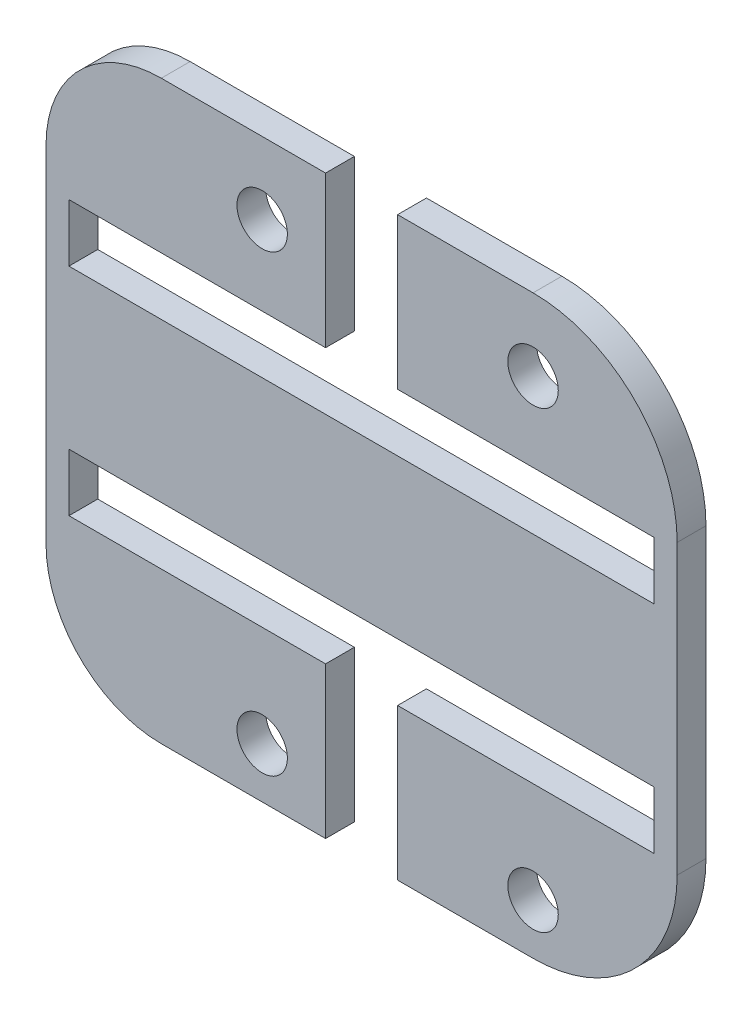
SolidWorks part; units mm, degrees
ref_plane "Alzado" through (0, 0, 0) normal (0, 0, 1) x (1, 0, 0)
ref_plane "Planta" through (0, 0, 0) normal (0, 1, 0) x (1, 0, 0)
ref_plane "Vista lateral" through (0, 0, 0) normal (1, 0, 0) x (0, 0, -1)
sketch "Croquis2" plane through (0, 0, 0) normal (0, 0, 1) x (1, 0, 0)
  line L1 (0, 0) -> (43.8, 0)
  line L2 (0, 0) -> (0, 40)
  line L3 (0, 40) -> (43.8, 40)
  line L4 (43.8, 0) -> (43.8, 40)
  line L5 (0, 0) -> (43.8, 40) construction
  line L6 (0, 40) -> (43.8, 0) construction
  line L7 (1.59, 29.5) -> (19.4, 29.5)
  line L8 (1.59, 29.5) -> (1.59, 25.5)
  line L9 (1.59, 25.5) -> (42.21, 25.5)
  line L10 (42.21, 29.5) -> (42.21, 25.5)
  line L11 (1.59, 29.5) -> (42.21, 25.5) construction
  line L12 (1.59, 25.5) -> (42.21, 29.5) construction
  line L16 (21.9, 40) -> (21.9, 0) construction
  line L17 (24.4, 29.5) -> (42.21, 29.5)
  line L18 (0, 20) -> (43.8, 20) construction
  line L19 (24.4, 0) -> (19.4, 0)
  line L20 (24.4, 0) -> (24.4, 10.5)
  line L21 (24.4, 40) -> (19.4, 40)
  line L22 (19.4, 0) -> (19.4, 10.5)
  line L23 (24.4, 0) -> (19.4, 40) construction
  line L24 (24.4, 40) -> (19.4, 0) construction
  line L25 (19.4, 29.5) -> (19.4, 40)
  line L26 (24.4, 29.5) -> (24.4, 40)
  line L27 (24.4, 10.5) -> (24.4, 0)
  line L28 (24.4, 10.5) -> (42.21, 10.5)
  line L29 (42.21, 10.5) -> (42.21, 14.5)
  line L30 (1.59, 14.5) -> (42.21, 14.5)
  line L31 (1.59, 10.5) -> (1.59, 14.5)
  line L32 (1.59, 10.5) -> (19.4, 10.5)
  line L33 (19.4, 10.5) -> (19.4, 0)
  line L34 (24.4, 0) -> (19.4, 0)
  point P4 (21.9, 20)
  point P10 (21.9, 27.5)
  point P13 (21.9, 20)
  dimension "D1" = 43.8
  dimension "D2" = 40
  dimension "D3" = 1.59
  dimension "D4" = 1.59
  dimension "D5" = 4
  dimension "D6" = 11
  dimension "D7" = 5
extrude "Saliente-Extruir1" add sketch "Croquis2" along normal blind 2 contours L32 L31 L30 L29 L28 L20 L1 L4 L3 L26 L17 L10 L9 L8 L7 L25 L2 L22
sketch "Croquis4" plane through (0, 0, 2) normal (0, 0, 1) x (1, 0, 0)
  line L0 (15, 35) -> (15, 3.5) construction
  line L2 (0, 40) -> (19.4, 40) construction
  line L4 (0, 0) -> (0, 40) construction
  line L5 (33.8, 35) -> (33.8, 3.5) construction
  line L6 (43.8, 0) -> (43.8, 40) construction
  line L7 (15, 35) -> (45.5713, 35) construction
  circle A0 centre (15, 35) radius 1.75
  circle A1 centre (15, 3.5) radius 1.75
  circle A2 centre (33.8, 35) radius 1.75
  circle A3 centre (33.8, 3.5) radius 1.75
  point P16 (0, 0)
  point P17 (0, 0)
  dimension "D2" = 3.5
  dimension "D1" = 15
  dimension "D3" = 31.5
  dimension "D4" = 5
  dimension "D5" = 10
extrude "Cortar-Extruir1" cut sketch "Croquis4" against normal blind 2 contours A0 | A1 | A3 | A2
fillet "Redondeo1" radius 10 2 edges at (43.8, 40, 1) (43.8, 0, 1)
fillet "Redondeo2" radius 8 2 edges at (0, 0, 1) (0, 40, 1)
